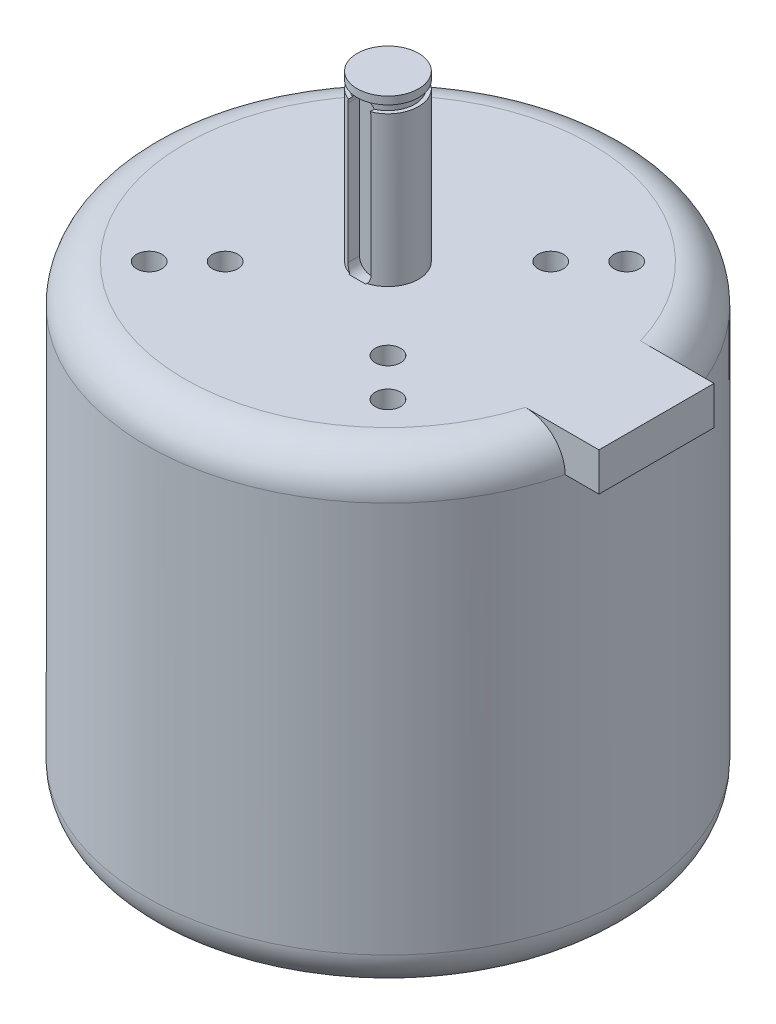
SolidWorks part; units mm, degrees
ref_plane "정면" through (0, 0, 0) normal (0, 0, 1) x (1, 0, 0)
ref_plane "윗면" through (0, 0, 0) normal (0, 1, 0) x (1, 0, 0)
ref_plane "우측면" through (0, 0, 0) normal (1, 0, 0) x (0, 0, -1)
sketch "스케치1" plane through (0, 0, 0) normal (0, 0, 1) x (1, 0, 0)
  line L0 (0, 0) -> (0, 82.5) construction
  line L1 (0, 82.5) -> (4, 82.5)
  line L2 (4, 82.5) -> (4, 61)
  line L3 (4, 61) -> (31.5, 61)
  line L4 (31.5, 61) -> (31.5, 0)
  line L5 (31.5, 0) -> (0, 0)
  line L6 (0, 0) -> (0, 82.5)
  dimension "D1" = 63
  dimension "D2" = 61
  dimension "D3" = 8
  dimension "D4" = 21.5
revolve "회전1" add sketch "스케치1" angle 360 about L0
fillet "필렛1" radius 5 2 edges at (0, 0, -31.5) (0, 61, -31.5)
sketch "스케치3" plane through (0, 0, 0) normal (1, 0, 0) x (0, 0, -1)
  line L0 (-31.5, 56) -> (31.5, 56) construction
  line L1 (-7.5, 56) -> (7.5, 56)
  line L2 (-7.5, 56) -> (-7.5, 61)
  line L3 (-7.5, 61) -> (7.5, 61)
  line L4 (7.5, 56) -> (7.5, 61)
  line L5 (26.5, 61) -> (-26.5, 61) construction
  line L6 (0, 56) -> (0, 61) construction
  point P6 (0, 56)
  dimension "D1" = 15
extrude "보스-돌출1" add sketch "스케치3" along normal blind 35
hole_wizard "M4x0.7 나사 구멍1" positions "스케치4" profile "스케치5" tap size "M4x0.7" standard "Ansi Metric"
sketch "스케치4" plane through (0, 61, 0) normal (0, 1, 0) x (1, 0, 0)
  circle A0 centre (0, 0) radius 15 construction
  circle A2 centre (0, 0) radius 22 construction
  point P0 (10.6066, 10.6066)
  point P2 (15.5563, 15.5563)
  point P20 (10.6066, -10.6066)
  point P21 (15.5563, -15.5563)
  point P22 (-10.6066, -10.6066)
  point P23 (-15.5563, -15.5563)
  point P24 (-10.6066, 10.6066)
  point P25 (-15.5563, 15.5563)
  point P26 (0, 0)
  dimension "D1" = 30
  dimension "D2" = 44
  dimension "D3" = 4
sketch "스케치5" plane through (10.6066, 61, -10.6066) normal (1, 0, 0) x (0, 0, 1)
  line L0 (0, 0) -> (0, 12.4914)
  line L1 (0, 12.4914) -> (1.65, 11.5)
  line L2 (1.65, 11.5) -> (1.65, 0)
  line L5 (1.65, 0) -> (0, 0)
  line L10 (0, 12.4914) -> (-1.65, 11.5) construction
  line L11 (0, -6.35) -> (0, 107.95) construction
  dimension "탭 드릴 지름" = 3.3
  dimension "탭 드릴 깊이" = 11.5
  dimension "드릴 각도" = 118
cosmetic thread "구멍 나사산1" parameters "D1"=8, "D2"=4
cosmetic thread "구멍 나사산2" parameters "D1"=8, "D2"=4
cosmetic thread "구멍 나사산3" parameters "D1"=8, "D2"=4
cosmetic thread "구멍 나사산4" parameters "D1"=8, "D2"=4
cosmetic thread "구멍 나사산5" parameters "D1"=8, "D2"=4
cosmetic thread "구멍 나사산6" parameters "D1"=8, "D2"=4
cosmetic thread "구멍 나사산7" parameters "D1"=8, "D2"=4
cosmetic thread "구멍 나사산8" parameters "D1"=8, "D2"=4
sketch "스케치6" plane through (0, 0, 0) normal (1, 0, 0) x (0, 0, -1)
  line L0 (0, 82.5) -> (0, 61) construction
  line L1 (4, 82.5) -> (-4, 82.5) construction
  line L2 (7.5, 61) -> (-7.5, 61) construction
  line L3 (4, 61) -> (4, 82.5) construction
  line L4 (4, 80.5) -> (3.5, 80.5)
  line L5 (4, 80.5) -> (4, 81.5)
  line L6 (4, 81.5) -> (3.5, 81.5)
  line L7 (3.5, 80.5) -> (3.5, 81.5)
  dimension "D1" = 1
  dimension "D2" = 1
  dimension "D3" = 0.5
revolve "컷-회전1" cut sketch "스케치6" angle 360 about L0
sketch "Sketch2" plane through (-5.6914, 82.5, 0.7546) normal (0, 1, 0) x (-1, 0, 0)
  line L0 (-5.6914, 3.2454) -> (-5.6914, -0.7546) construction
  line L1 (-5.6914, -0.7546) -> (-5.6914, 3.2454) construction
  circle A0 centre (-5.6914, -0.7546) radius 4 construction
  circle A2 centre (-5.6914, -0.7546) radius 4
  dimension "Angle from vertical" = 360
ref_plane "Plane1" through (0, 82.5, 4) normal (0, 0, -1) x (-1, 0, 0)
sketch "Sketch3" plane through (2.8457, 82.5, 4) normal (0, 0, -1) x (0, 1, 0)
  line L0 (-2.5, -2.8457) -> (-20.5, -2.8457) construction
  line L1 (-2.5, -1.3457) -> (-20.5, -1.3457)
  line L2 (-2.5, -4.3457) -> (-20.5, -4.3457)
  arc A0 (-2.5, -1.3457) -> (-2.5, -4.3457) centre (-2.5, -2.8457) cw
  arc A1 (-20.5, -1.3457) -> (-20.5, -4.3457) centre (-20.5, -2.8457) ccw
  dimension "Keyway width" = 3
  dimension "Distance from end face" = 2.5
  dimension "Length of slot" = 18
extrude "Cut-Extrude1" cut sketch "Sketch3" along normal blind 1.8
other "keyway (bs 4235 - part i)<1>"
